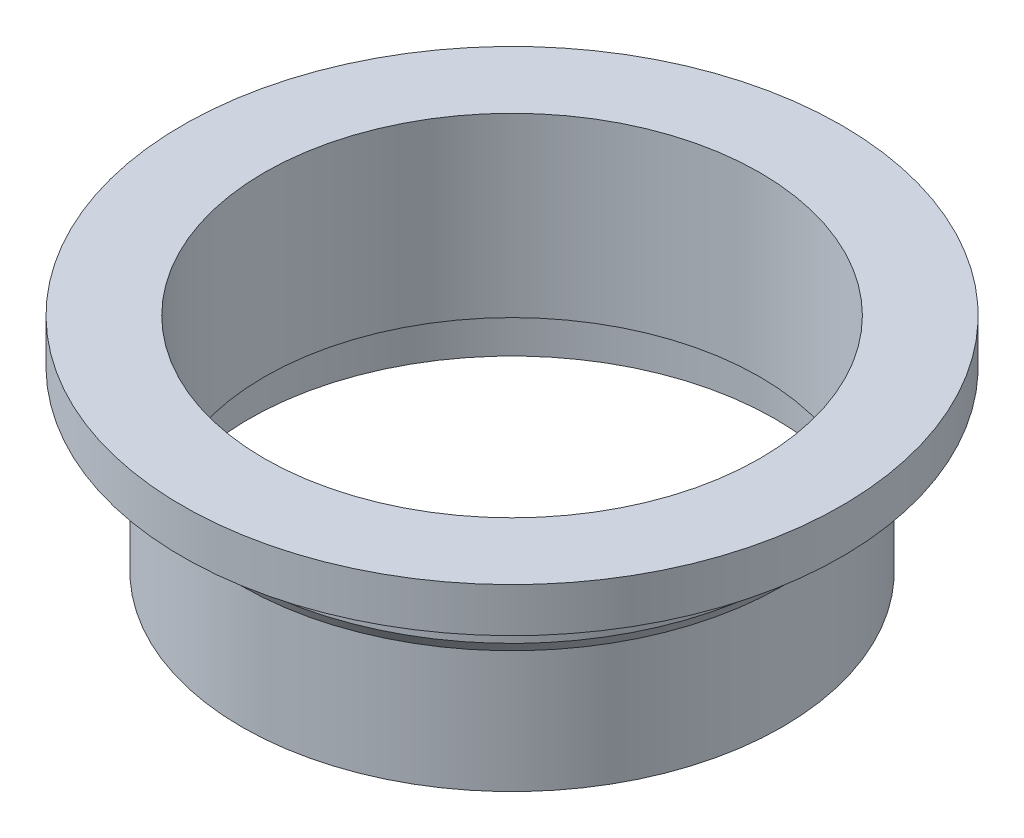
SolidWorks part; units mm, degrees
ref_plane "Front" through (0, 0, 0) normal (0, 0, 1) x (1, 0, 0)
ref_plane "Top" through (0, 0, 0) normal (0, 1, 0) x (1, 0, 0)
ref_plane "Right" through (0, 0, 0) normal (1, 0, 0) x (0, 0, -1)
ref_axis "Axis1" through (0, 50, 0) along (0, -1, 0)
sketch "Sketch1" plane through (0, 0, 0) normal (0, 0, 1) x (1, 0, 0)
  line L0 (0, 0) -> (0, 50) construction
  line L1 (59.5, 0) -> (59.5, 50)
  line L2 (59.5, 50) -> (74.5, 50)
  line L3 (74.5, 50) -> (74.5, 40)
  line L4 (74.5, 40) -> (63.8397, 40)
  line L5 (63.8397, 40) -> (62.5, 35)
  line L6 (62.5, 35) -> (62.5, 0)
  line L7 (62.5, 0) -> (59.5, 0)
  dimension "D1" = 59.5
  dimension "D2" = 3
  dimension "D3" = 10
  dimension "D4" = 5
  dimension "D5" = 15
  dimension "D6" = 15
  dimension "D7" = 50
revolve "Revolve1" add sketch "Sketch1" angle 360 about L0
sketch "Sketch3" plane through (0, 40, 0) normal (0, -1, 0) x (1, 0, 0)
  line L1 (1.375, -72.487) -> (1.375, -62.5)
  line L2 (1.375, -62.5) -> (-1.375, -62.5)
  line L3 (-1.375, -62.5) -> (-1.375, -72.487)
  circle A0 centre (0, 0) radius 62.5 construction
  arc A1 (-1.375, -72.487) -> (1.375, -72.487) centre (0, 0) ccw
  circle A2 centre (0, 0) radius 74.5 construction
  point P2 (0, -62.5)
  dimension "D1" = 2
  dimension "D2" = 2.75
extrude "Boss-Extrude1" add sketch "Sketch3" along normal blind 3
sketch "Sketch4" plane through (0, 50, 0) normal (0, 1, 0) x (1, 0, 0)
  circle A0 centre (0, 0) radius 56
  circle A1 centre (0, 0) radius 59.5
  circle A2 centre (0, 0) radius 59.5 construction
  dimension "D1" = 112
extrude "Boss-Extrude2" add sketch "Sketch4" against normal offset from surface (40 mm away) 10 up to face at (0, 0, -62.5)
sketch "Sketch5" plane through (0, 0, 0) normal (0, 0, 1) x (1, 0, 0)
  line L0 (62.5, 30) -> (61.1, 27.5751)
  line L1 (62.5, 0) -> (62.5, 35) construction
  line L2 (61.1, 27.5751) -> (61.1, 0)
  line L3 (-62.5, 0) -> (62.5, 0) construction
  line L4 (61.1, 0) -> (62.5, 0)
  line L5 (62.5, 0) -> (62.5, 30)
  line L6 (62.5, 35) -> (-62.5, 35) construction
  line L7 (59.5, 0) -> (59.5, 10) construction
  dimension "D1" = 5
  dimension "D2" = 1.6
  dimension "D3" = 30
revolve "Cut-Revolve1" cut sketch "Sketch5" angle 360 about axis through (0, 50, 0) along (0, -1, 0)
fillet "Fillet1" radius 1 2 edges at (1.375, 38.5, -72.487) (-1.375, 38.5, -72.487)
